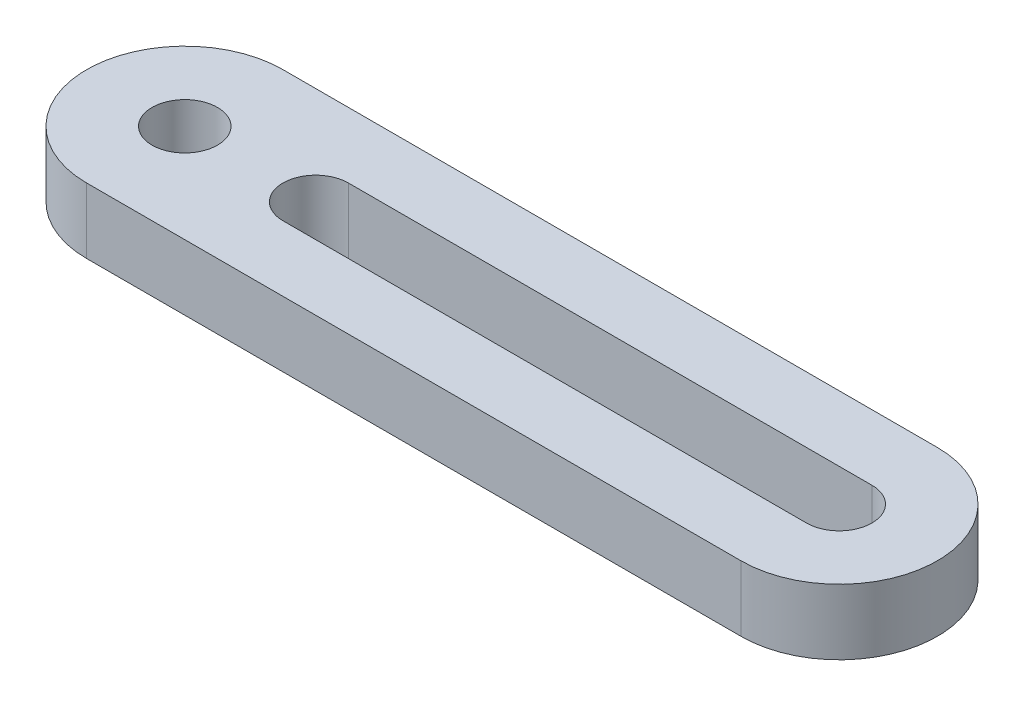
SolidWorks part; units mm, degrees
ref_plane "Front Plane" through (0, 0, 0) normal (0, 0, 1) x (1, 0, 0)
ref_plane "Top Plane" through (0, 0, 0) normal (0, 1, 0) x (1, 0, 0)
ref_plane "Right Plane" through (0, 0, 0) normal (1, 0, 0) x (0, 0, -1)
sketch "Sketch1" plane through (0, 0, 0) normal (0, 1, 0) x (1, 0, 0)
  line L0 (-39.4188, 7.1219) -> (10.5812, 7.1219) construction
  line L1 (-39.4188, 14.6219) -> (10.5812, 14.6219)
  line L2 (-39.4188, -0.3781) -> (10.5812, -0.3781)
  arc A0 (-39.4188, 14.6219) -> (-39.4188, -0.3781) centre (-39.4188, 7.1219) ccw
  arc A1 (10.5812, -0.3781) -> (10.5812, 14.6219) centre (10.5812, 7.1219) ccw
  point P2 (-14.4188, 7.1219)
  dimension "D1" = 7.5
  dimension "D2" = 50
extrude "Boss-Extrude1" add sketch "Sketch1" along normal blind 5
sketch "Sketch3" plane through (0, 5, 0) normal (0, 1, 0) x (1, 0, 0)
  line L0 (-29.4195, 7.1219) -> (10.5812, 7.1219) construction
  line L1 (-29.4195, 9.6219) -> (10.5812, 9.6219)
  line L2 (-29.4195, 4.6219) -> (10.5812, 4.6219)
  arc A0 (-29.4195, 9.6219) -> (-29.4195, 4.6219) centre (-29.4195, 7.1219) ccw
  arc A1 (10.5812, 4.6219) -> (10.5812, 9.6219) centre (10.5812, 7.1219) ccw
  arc A2 (10.5812, -0.3781) -> (10.5812, 14.6219) centre (10.5812, 7.1219) ccw construction
  circle A5 centre (-39.4188, 7.1219) radius 2.5
  arc A6 (-39.4188, 14.6219) -> (-39.4188, -0.3781) centre (-39.4188, 7.1219) ccw construction
  point P2 (-9.4192, 7.1219)
  dimension "D1" = 2.5
  dimension "D3" = 5
  dimension "D2" = 0
  dimension "D4" = 40.0007
  dimension "D5" = 0
extrude "Cut-Extrude1" cut sketch "Sketch3" against normal blind 5
